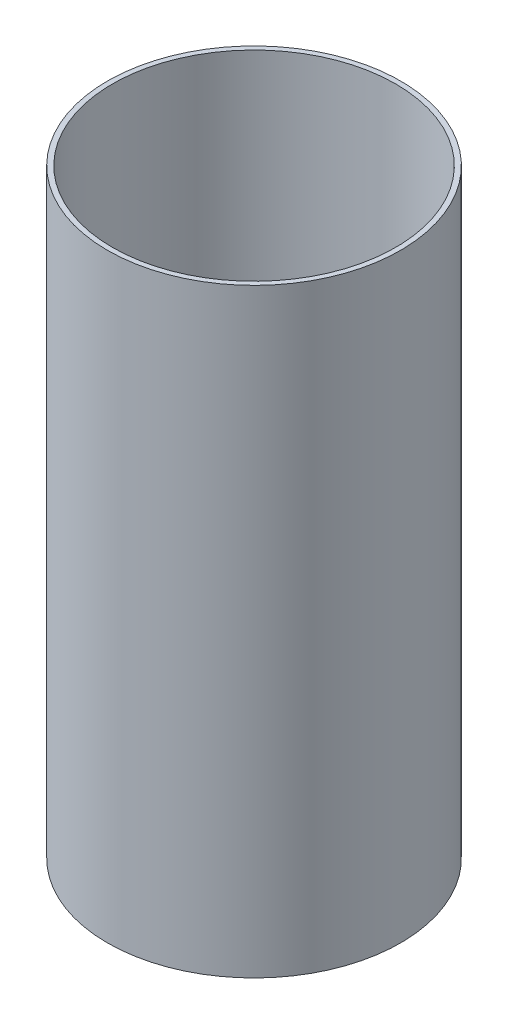
SolidWorks part; units mm, degrees
ref_plane "Front Plane" through (0, 0, 0) normal (0, 0, 1) x (1, 0, 0)
ref_plane "Top Plane" through (0, 0, 0) normal (0, 1, 0) x (1, 0, 0)
ref_plane "Right Plane" through (0, 0, 0) normal (1, 0, 0) x (0, 0, -1)
sketch "Sketch1" plane through (0, 0, 0) normal (0, 1, 0) x (1, 0, 0)
  circle A0 centre (0, 0) radius 88
  circle A1 centre (0, 0) radius 85
extrude "Boss-Extrude1" add sketch "Sketch1" along normal blind 360
ref_plane "Plane2" through (0, 35, 0) normal (0, -1, 0) x (-1, 0, 0)
ref_plane "Plane1" through (-88, 0, 0) normal (-1, 0, 0) x (0, 0, 1)
sketch "Sketch2" plane through (-88, 0, 0) normal (-1, 0, 0) x (0, 0, 1)
  line L0 (-88, 0) -> (88, 0) construction
  circle A0 centre (0, 35) radius 2.75
  dimension "D1" = 35
extrude "Cut-Extrude1" cut sketch "Sketch2" against normal up to next
sketch "Sketch4" plane through (0, 35, 0) normal (0, -1, 0) x (1, 0, 0)
  line L0 (-88, 0) -> (-88, -5)
  line L1 (-88, 0) -> (-42.5101, 0) construction
  line L2 (-88, -5) -> (-83, 0)
  line L5 (-88, 0) -> (-83, 0)
  point P3 (-88, 0)
revolve "Cut-Revolve1" cut sketch "Sketch4" angle 360 about L5
